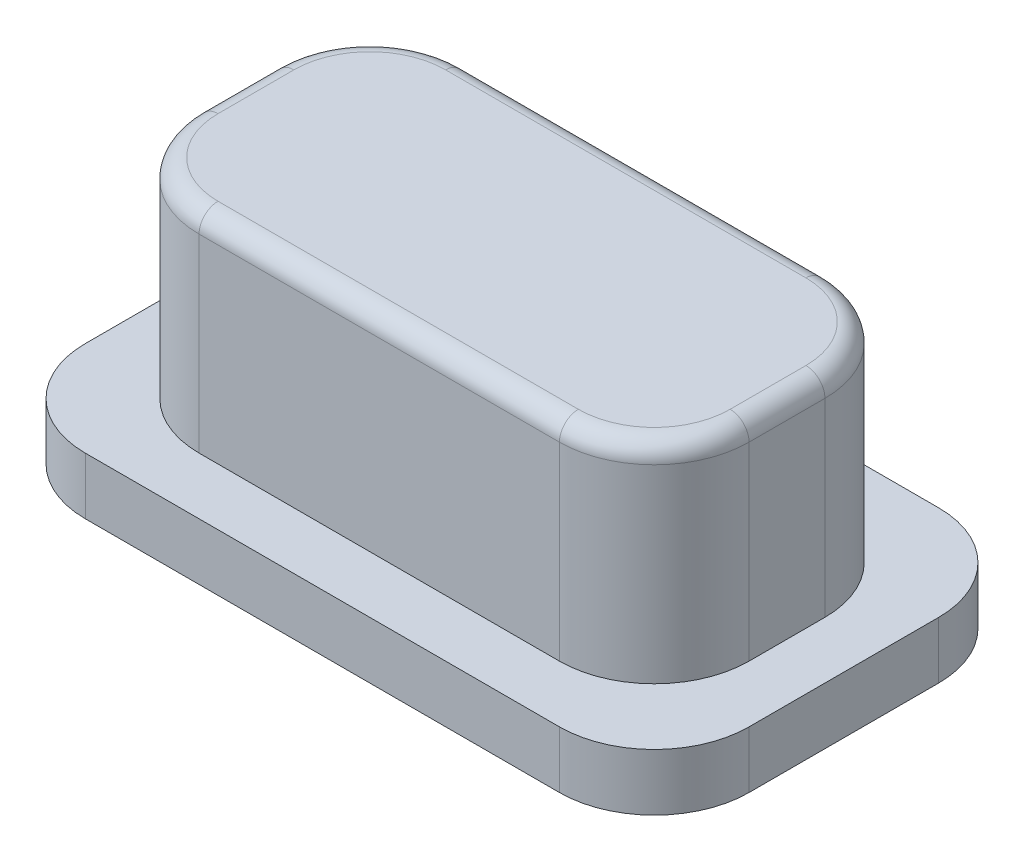
SolidWorks part; units mm, degrees
ref_plane "前视基准面" through (0, 0, 0) normal (0, 0, 1) x (1, 0, 0)
ref_plane "上视基准面" through (0, 0, 0) normal (0, 1, 0) x (1, 0, 0)
ref_plane "右视基准面" through (0, 0, 0) normal (1, 0, 0) x (0, 0, -1)
sketch "草图1" plane through (0, 0, 0) normal (0, 1, 0) x (1, 0, 0)
  line L1 (-2.5031, 1.7604) -> (4.4969, 1.7604)
  line L2 (-2.5031, 1.7604) -> (-2.5031, -2.2396)
  line L3 (-2.5031, -2.2396) -> (4.4969, -2.2396)
  line L4 (4.4969, 1.7604) -> (4.4969, -2.2396)
  dimension "D1" = 7
  dimension "D2" = 4
extrude "凸台-拉伸1" add sketch "草图1" along normal blind 0.6
sketch "草图2" plane through (0, 0.6, 0) normal (0, 1, 0) x (1, 0, 0)
  line L0 (4.4969, 1.7604) -> (-2.5031, 1.7604) construction
  line L1 (-1.9031, 1.1604) -> (3.8969, 1.1604)
  line L2 (-1.9031, 1.1604) -> (-1.9031, -1.6396)
  line L3 (-1.9031, -1.6396) -> (3.8969, -1.6396)
  line L4 (3.8969, 1.1604) -> (3.8969, -1.6396)
  line L5 (-1.9031, 1.1604) -> (3.8969, -1.6396) construction
  line L6 (-1.9031, -1.6396) -> (3.8969, 1.1604) construction
  line L7 (-2.5031, 1.7604) -> (-2.5031, -2.2396) construction
  point P0 (0.9969, -0.2396)
  point P8 (0.9969, 1.7604)
  point P12 (-2.5031, -0.2396)
  dimension "D1" = 5.8
  dimension "D2" = 2.8
extrude "凸台-拉伸2" add sketch "草图2" along normal blind 2.2
fillet "圆角1" radius 1 8 edges at (4.4969, 0.3, -1.7604) (4.4969, 0.3, 2.2396) (-2.5031, 0.3, -1.7604) (-2.5031, 0.3, 2.2396) (3.8969, 1.7, -1.1604) (-1.9031, 1.7, -1.1604) (-1.9031, 1.7, 1.6396) (3.8969, 1.7, 1.6396)
sketch "草图3" plane through (0, 0, 0) normal (0, -1, 0) x (-1, 0, 0)
  line L0 (1.5031, -2.2396) -> (-3.4969, -2.2396) construction
  line L1 (-2.4969, 0.5604) -> (0.5031, 0.5604)
  line L2 (-2.4969, 0.5604) -> (-2.4969, -1.0396)
  line L3 (-2.4969, -1.0396) -> (0.5031, -1.0396)
  line L4 (0.5031, 0.5604) -> (0.5031, -1.0396)
  line L5 (-2.4969, 0.5604) -> (0.5031, -1.0396) construction
  line L6 (-2.4969, -1.0396) -> (0.5031, 0.5604) construction
  line L7 (2.5031, 0.7604) -> (2.5031, -1.2396) construction
  point P0 (-0.9969, -0.2396)
  point P7 (-0.9969, -2.2396)
  point P11 (2.5031, -0.2396)
  dimension "D1" = 3
  dimension "D2" = 1.6
extrude "凸台-拉伸3" add sketch "草图3" along normal blind 0.1
fillet "圆角2" radius 0.2 8 edges at (3.604, 2.8, -0.8675) (3.604, 2.8, 1.3468) (0.9969, 2.8, 1.6396) (-1.6102, 2.8, 1.3468) (-1.6102, 2.8, -0.8675) (0.9969, 2.8, -1.1604) (-1.9031, 2.8, 0.2396) (3.8969, 2.8, 0.2396)
